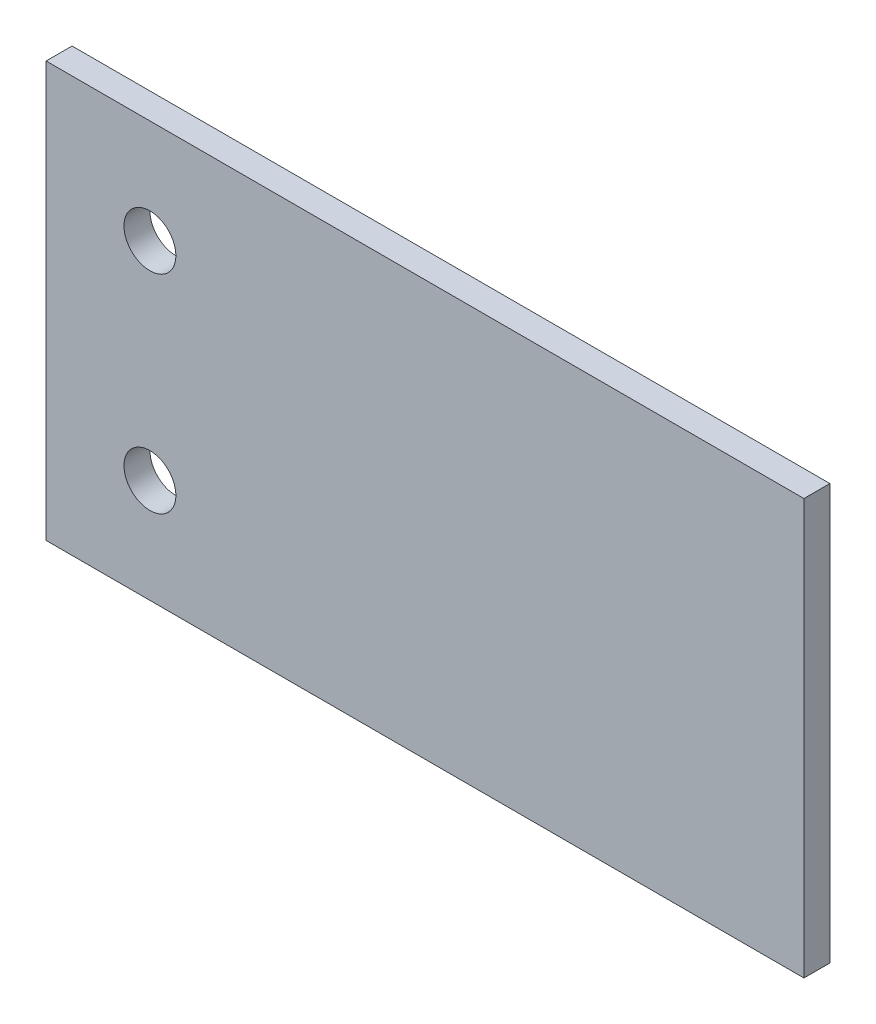
SolidWorks part; units mm, degrees
ref_plane "FRONT" through (0, 0, 0) normal (0, 0, 1) x (1, 0, 0)
ref_plane "TOP" through (0, 0, 0) normal (0, 1, 0) x (1, 0, 0)
ref_plane "RIGHT" through (0, 0, 0) normal (1, 0, 0) x (0, 0, -1)
sketch "Sketch1" plane through (0, 0, 0) normal (0, 0, 1) x (1, 0, 0)
  line L1 (0, 0) -> (92.71, 0)
  line L2 (0, 0) -> (0, 50.8)
  line L3 (0, 50.8) -> (92.71, 50.8)
  line L4 (92.71, 0) -> (92.71, 50.8)
  circle A0 centre (12.7, 38.1) radius 3.175
  circle A1 centre (12.7, 12.7) radius 3.175
  dimension "D4" = 6.35
  dimension "D5" = 6.35
  dimension "D6" = 12.7
  dimension "D8" = 12.7
  dimension "D1" = 50.8
  dimension "D2" = 92.71
  dimension "D3" = 25.4
  dimension "D7" = 12.7
extrude "Boss-Extrude1" add sketch "Sketch1" along normal blind 3.175
